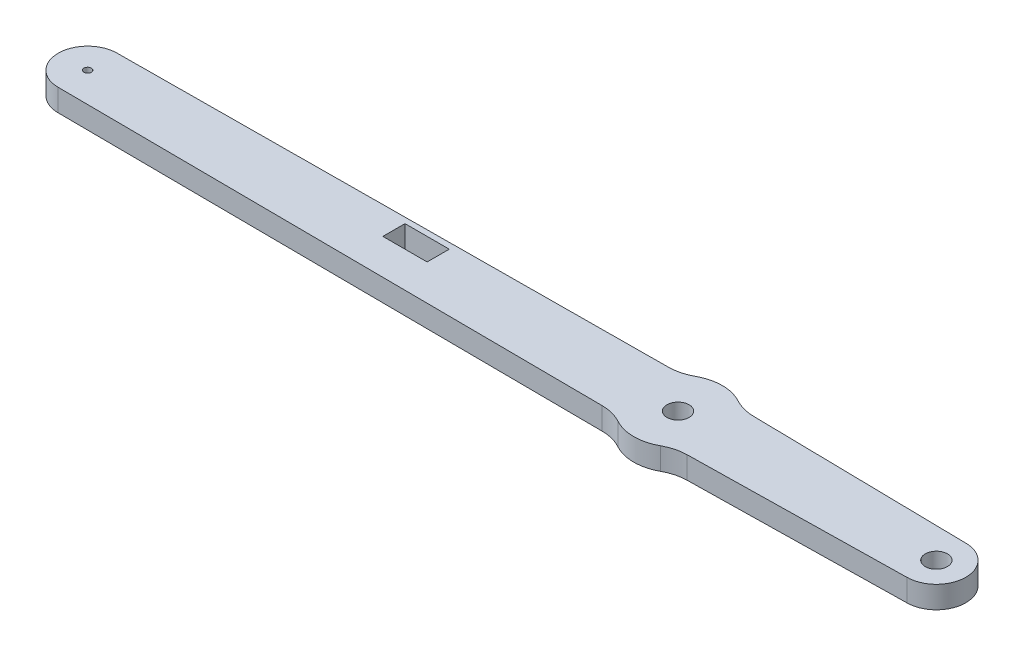
SolidWorks part; units mm, degrees
ref_plane "Alzado" through (0, 0, 0) normal (0, 0, 1) x (1, 0, 0)
ref_plane "Planta" through (0, 0, 0) normal (0, 1, 0) x (1, 0, 0)
ref_plane "Vista lateral" through (0, 0, 0) normal (1, 0, 0) x (0, 0, -1)
sketch "Croquis1" plane through (0, 0, 0) normal (0, 0, 1) x (1, 0, 0)
  line L0 (41932.2646, -390.2108) -> (41903.0663, -389.7065)
  line L1 (41856.7646, -390.7108) -> (41862.7646, -390.7108)
  line L2 (41856.7646, -390.7108) -> (41856.7646, -393.7108)
  line L3 (41856.7646, -393.7108) -> (41862.7646, -393.7108)
  line L4 (41862.7646, -390.7108) -> (41862.7646, -393.7108)
  line L5 (41932.2646, -398.2108) -> (41902.9628, -398.716)
  line L6 (41891.4577, -398.7122) -> (41817.2646, -398.2108)
  line L7 (41817.2646, -390.2108) -> (41891.4983, -389.7092)
  circle A0 centre (41817.2646, -394.2108) radius 0.5
  arc A1 (41817.2646, -390.2108) -> (41817.2646, -398.2108) centre (41817.2646, -394.2108) ccw
  circle A2 centre (41932.2646, -394.2108) radius 1.5
  arc A3 (41932.2646, -398.2108) -> (41932.2646, -390.2108) centre (41932.2646, -394.2108) ccw
  circle A4 centre (41897.2646, -394.2108) radius 1.5
  arc A5 (41900.1654, -388.9586) -> (41894.3612, -388.96) centre (41897.2646, -394.2108) ccw
  arc A6 (41900.1654, -388.9586) -> (41903.0663, -389.7065) centre (41903.0663, -383.7065) ccw
  arc A7 (41891.4983, -389.7092) -> (41894.3612, -388.96) centre (41891.4577, -383.7093) ccw
  arc A8 (41902.9628, -398.716) -> (41900.1654, -399.4629) centre (41903.0663, -404.7151) ccw
  arc A9 (41894.3612, -399.4615) -> (41891.4577, -398.7122) centre (41891.4577, -404.7122) ccw
  arc A10 (41894.3612, -399.4615) -> (41900.1654, -399.4629) centre (41897.2646, -394.2108) ccw
extrude "Saliente-Extruir1" add sketch "Croquis1" along normal blind 3
move or copy body "Sólido-Mover/Copiar1" bodies to move or copy 101 copy no rotation origin (0, -394.2108, 1.5) rotation axis (-1, 0, 0) rotation angle 90
